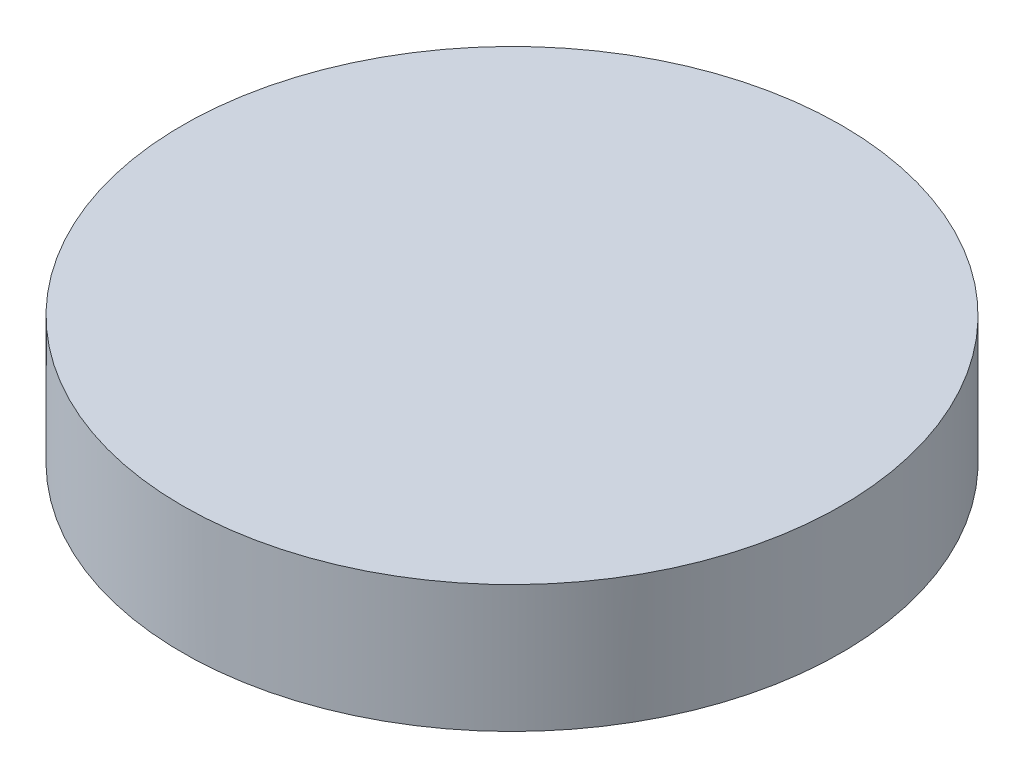
SolidWorks part; units mm, degrees
material "Water"
ref_plane "Front Plane" through (0, 0, 0) normal (0, 0, 1) x (1, 0, 0)
ref_plane "Top Plane" through (0, 0, 0) normal (0, 1, 0) x (1, 0, 0)
ref_plane "Right Plane" through (0, 0, 0) normal (1, 0, 0) x (0, 0, -1)
sketch "Sketch1" plane through (0, 0, 0) normal (0, 1, 0) x (1, 0, 0)
  circle A0 centre (0, 0) radius 31
  dimension "D1" = 62
extrude "Boss-Extrude1" add sketch "Sketch1" along normal blind 7.5
sketch "Sketch2" plane through (0, 7.5, 0) normal (0, 1, 0) x (1, 0, 0)
  circle A0 centre (0, 0) radius 13.5
  dimension "D1" = 27
sketch "Sketch3" plane through (0, 0, 0) normal (0, -1, 0) x (1, 0, 0)
  circle A0 centre (0, 0) radius 27.13
  circle A1 centre (0, 0) radius 31
  circle A2 centre (0, 0) radius 31
  dimension "D2" = 54.26
  dimension "D1" = 0
extrude "Boss-Extrude2" add sketch "Sketch3" along normal blind 4.47
